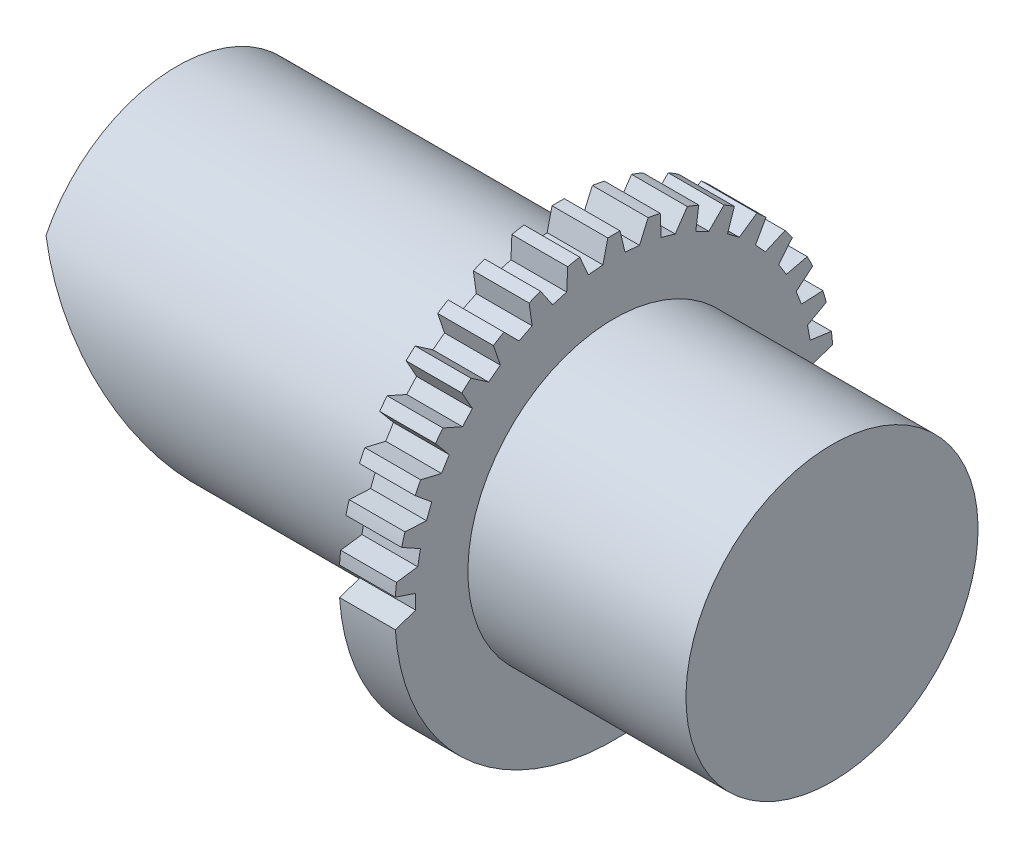
SolidWorks part; units mm, degrees
ref_plane "Front Plane" through (0, 0, 0) normal (1, 0, 0) x (0, 1, 0)
ref_plane "Top Plane" through (0, 0, 0) normal (0, 0, 1) x (0, 1, 0)
ref_plane "Right Plane" through (0, 0, 0) normal (0, 1, 0) x (-1, 0, 0)
sketch "Sketch2" plane through (0, 0, 0) normal (0, 0, 1) x (0, 1, 0)
  line L0 (0, -37.9236) -> (0, 103.8931) construction
  line L1 (0, -37.9236) -> (-25.4, -37.9236)
  line L2 (-25.4, -37.9236) -> (-25.4, 0)
  line L3 (-25.4, 0) -> (-38.1, 0)
  line L4 (-38.1, 0) -> (-38.1, 9.7014)
  line L5 (-38.1, 9.7014) -> (-25.4, 9.7014)
  line L6 (-25.4, 9.7014) -> (-25.4, 76.0236)
  line L7 (-25.4, 76.0236) -> (0, 76.0236)
  line L8 (0, 76.0236) -> (0, -37.9236)
  dimension "D1" = 25.4
  dimension "D2" = 12.7
  dimension "D3" = 25.4
revolve "Revolve1" add sketch "Sketch2" angle 360 about L8
sketch "Sketch3" plane through (-9.7014, 0, 0) normal (-1, 0, 0) x (0, -1, 0)
  line L6 (0, 0) -> (0, 43.6089) construction
  line L14 (0, 38.2888) -> (2.54, 38.2888)
  line L15 (2.54, 38.2888) -> (1.27, 34.4788)
  line L16 (1.27, 34.4788) -> (0, 34.4788)
  line L17 (0, 34.4788) -> (-1.27, 34.4788)
  line L18 (-1.27, 34.4788) -> (-2.54, 38.2888)
  line L19 (-2.54, 38.2888) -> (0, 38.2888)
  dimension "D1" = 2.54
  dimension "D2" = 2.54
  dimension "D3" = 1.27
  dimension "D4" = 1.27
  dimension "D5" = 3.81
extrude "Cut-Extrude1" cut sketch "Sketch3" against normal through all contours L19 L14 L15 L16 L17 L18
pattern_circular "CirPattern1" count 18 over 180 about axis through (0, 0, 0) along (1, 0, 0) of "Cut-Extrude1"
sketch "Sketch5" plane through (0, 0, 0) normal (0, 0, 1) x (0, 1, 0)
  line L0 (11.2912, 76.0236) -> (-25.4, 76.0236)
  line L2 (-25.4, 76.0236) -> (-25.4, 49.5362)
  line L3 (-25.4, 76.0236) -> (-25.4, 9.7014) construction
  line L4 (-25.4, 49.5362) -> (11.2912, 76.0236)
  line L5 (25.4, 76.0236) -> (-25.4, 76.0236) construction
extrude "Cut-Extrude2" cut sketch "Sketch5" against normal through all both and the other way through all
sketch "Sketch7" plane through (0, 0, 0) normal (0, 0, 1) x (0, 1, 0)
  line L0 (0, 67.8725) -> (-7.3749, 78.2118)
  line L1 (11.2912, 76.0236) -> (-25.4, 49.5362) construction
  line L2 (-14.3761, 57.4944) -> (-21.9788, 67.6673)
  line L3 (-7.0544, 62.7799) -> (-14.3761, 57.4944)
  line L4 (-7.0544, 62.7799) -> (0, 67.8725)
  line L5 (-21.9788, 67.6673) -> (-7.3749, 78.2118) construction
  arc A0 (-21.9788, 67.6673) -> (-7.3749, 78.2118) centre (-14.6697, 72.9297) cw
  dimension "D1" = 12.7
  dimension "D2" = 12.7
extrude "Boss-Extrude1" add sketch "Sketch7" along normal mid plane 7.62
sketch "Sketch9" plane through (0, 0, 3.81) normal (0, 0, 1) x (1, 0, 0)
  circle A0 centre (-72.9297, -14.6697) radius 6.35
  dimension "D1" = 12.7
extrude "Cut-Extrude4" cut sketch "Sketch9" against normal through all both and the other way through all
